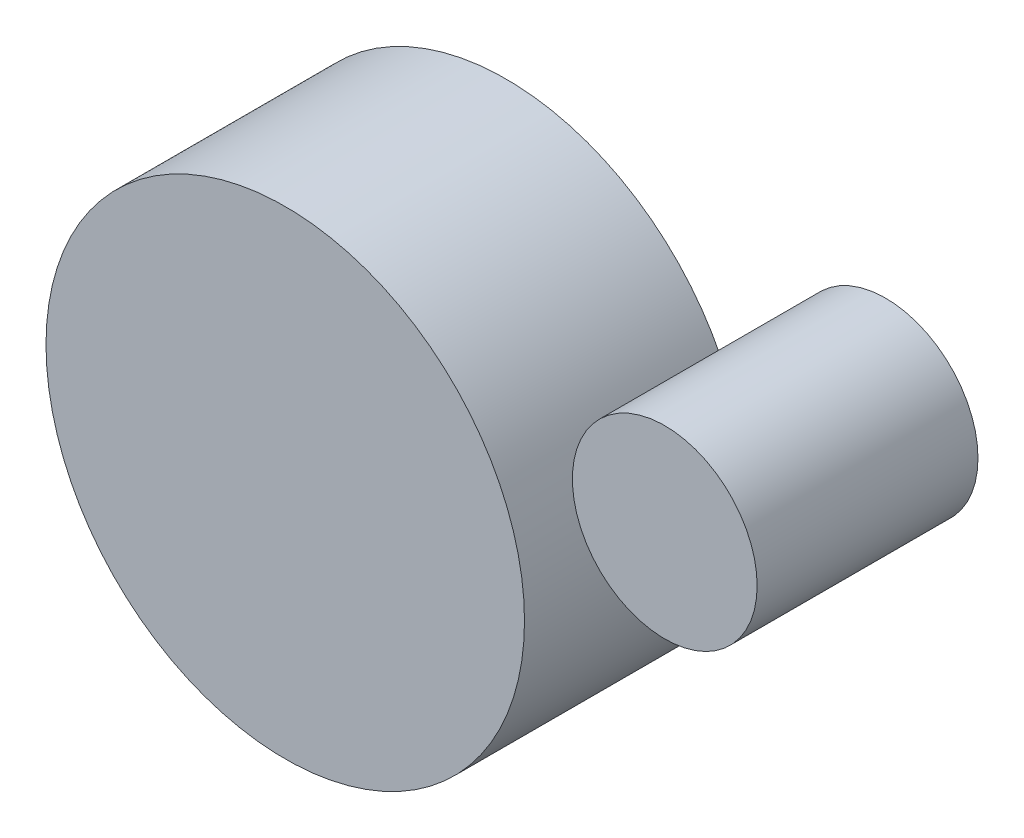
SolidWorks part; units mm, degrees
ref_plane "Alzado" through (0, 0, 0) normal (0, 0, 1) x (1, 0, 0)
ref_plane "Planta" through (0, 0, 0) normal (0, 1, 0) x (1, 0, 0)
ref_plane "Vista lateral" through (0, 0, 0) normal (1, 0, 0) x (0, 0, -1)
sketch "Croquis1" plane through (0, 0, 0) normal (0, 0, 1) x (1, 0, 0)
  line L4 (-981.3218, 39.55) -> (49018.6782, 39.55) construction
  line L5 (-103.5055, 39.55) -> (149.7175, 39.55) construction
  circle A0 centre (44.9, 27) radius 12.55
  circle A1 centre (-6.65, 7.05) radius 32.5
  dimension "D1" = 0
extrude "Saliente-Extruir1" add sketch "Croquis1" along normal blind 30
